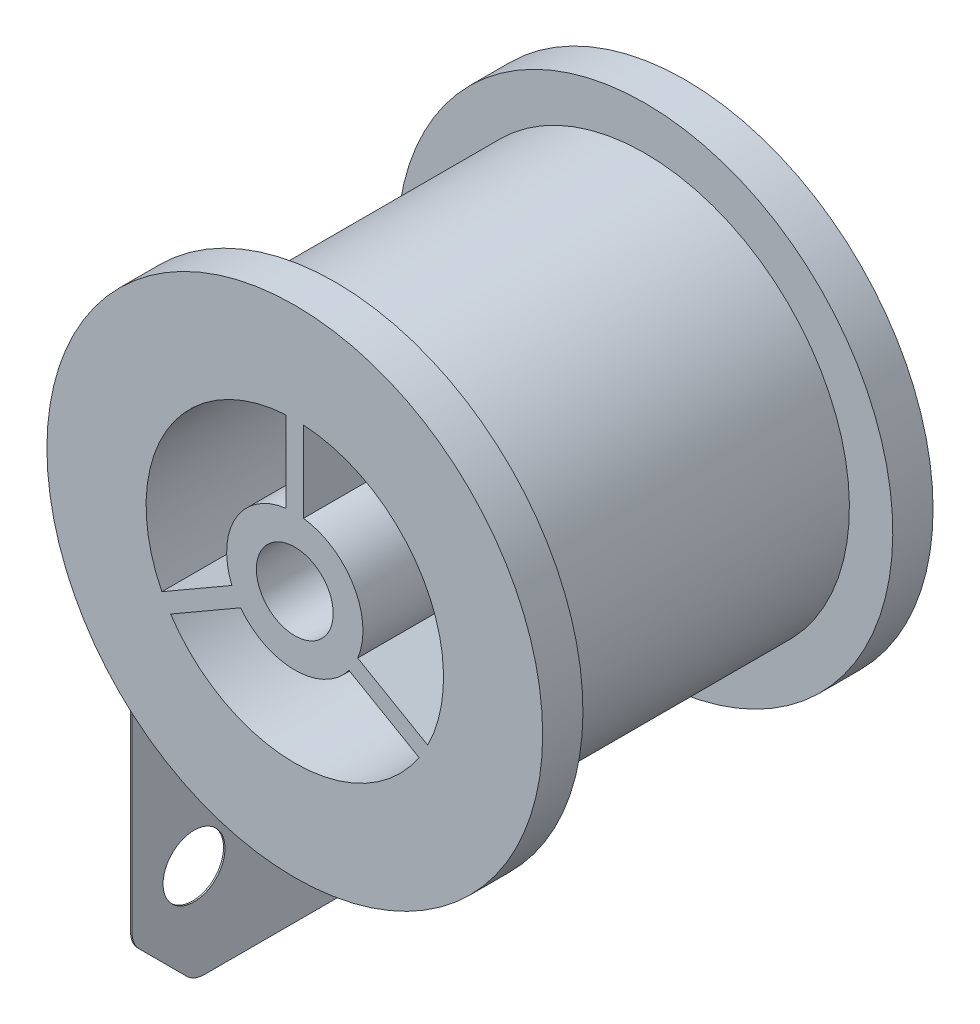
SolidWorks part; units mm, degrees
material "PTFE(普通)"
ref_plane "前视基准面" through (0, 0, 0) normal (0, 0, 1) x (1, 0, 0)
ref_plane "上视基准面" through (0, 0, 0) normal (0, 1, 0) x (1, 0, 0)
ref_plane "右视基准面" through (0, 0, 0) normal (1, 0, 0) x (0, 0, -1)
sketch "草图2" plane through (0, 0, 0) normal (0, 1, 0) x (1, 0, 0)
  line L0 (0, 15.75) -> (0, -15.75) construction
  line L1 (3.1, 15.75) -> (20, 15.75)
  line L2 (20, 15.75) -> (20, 12.5)
  line L3 (20, 12.5) -> (16.5, 12.5)
  line L4 (16.5, 12.5) -> (16.5, -12.5)
  line L5 (16.5, -12.5) -> (20, -12.5)
  line L6 (20, -12.5) -> (20, -15.75)
  line L7 (20, -15.75) -> (3.1, -15.75)
  line L8 (3.1, 15.75) -> (3.1, -15.75)
  point P3 (0, 0)
  point P12 (4.7044, -15.75)
  dimension "D1" = 31.5
  dimension "D2" = 33
  dimension "D3" = 6.2
  dimension "D4" = 40
  dimension "D5" = 25
revolve "旋转1" add sketch "草图2" angle 360 about L0
sketch "草图3" plane through (0, 0, 15.75) normal (0, 0, 1) x (1, 0, 0)
  line L0 (0, 12) -> (0, 5.5) construction
  line L1 (-0.7, 11.9796) -> (-0.7, 5.4553)
  line L2 (0.7, 11.9796) -> (0.7, 5.4553)
  line L3 (0.7, 12) -> (0.7, 5.5) construction
  line L4 (-0.7, 12) -> (-0.7, 5.5) construction
  line L5 (10.7246, -5.3836) -> (5.0744, -2.1214)
  line L6 (10.0246, -6.596) -> (4.3744, -3.3339)
  line L7 (-10.0246, -6.596) -> (-4.3744, -3.3339)
  line L8 (-10.7246, -5.3836) -> (-5.0744, -2.1214)
  circle A0 centre (0, 0) radius 5.5
  circle A1 centre (0, 0) radius 12
  point P18 (-8.1743, -2.1446)
  point P19 (0, 0)
  point P24 (0, 0)
  dimension "D1" = 24
  dimension "D2" = 11
  dimension "D3" = 0.7
  dimension "D4" = 0.7
  dimension "D5" = 3
extrude "切除-拉伸1" cut sketch "草图3" against normal blind 14.7 contours L1 A1 L8 A0 | L7 A1 L6 A0 | L5 A1 L2 A0
mirror "镜向2" about plane through (0, 0, 0) normal (0, 0, 1) of "切除-拉伸1"
ref_plane "基准面1" through (-16.5, 0, 0) normal (-1, 0, 0) x (0, 0, 1)
sketch "草图4" plane through (-16.5, 0, 0) normal (-1, 0, 0) x (0, 0, 1)
  line L0 (7.5, -31.5084) -> (-7.5, -31.5084) construction
  line L1 (-12.5, 0) -> (12.5, 0)
  line L2 (-12.5, 0) -> (-12.5, -39.5084)
  line L3 (-12.5, -39.5084) -> (12.5, -39.5084)
  line L4 (12.5, 0) -> (12.5, -39.5084)
  circle A0 centre (7.5, -31.5084) radius 2.5
  circle A1 centre (-7.5, -31.5084) radius 2.5
  point P4 (0, 0)
  point P9 (0, -31.5084)
  point P11 (12.5, -39.5084)
  dimension "D3" = 5
  dimension "D1" = 25
  dimension "D2" = 8
  dimension "D4" = 15
extrude "凸台-拉伸1" add sketch "草图4" against normal blind 0.12
chamfer "倒角1" distance 5 angle 45 2 edges at (-16.44, -39.5084, -12.5) (-16.44, -39.5084, 12.5)
fillet "圆角1" radius 2 4 edges at (-16.44, -34.5084, -12.5) (-16.44, -39.5084, -7.5) (-16.44, -39.5084, 7.5) (-16.44, -34.5084, 12.5)
